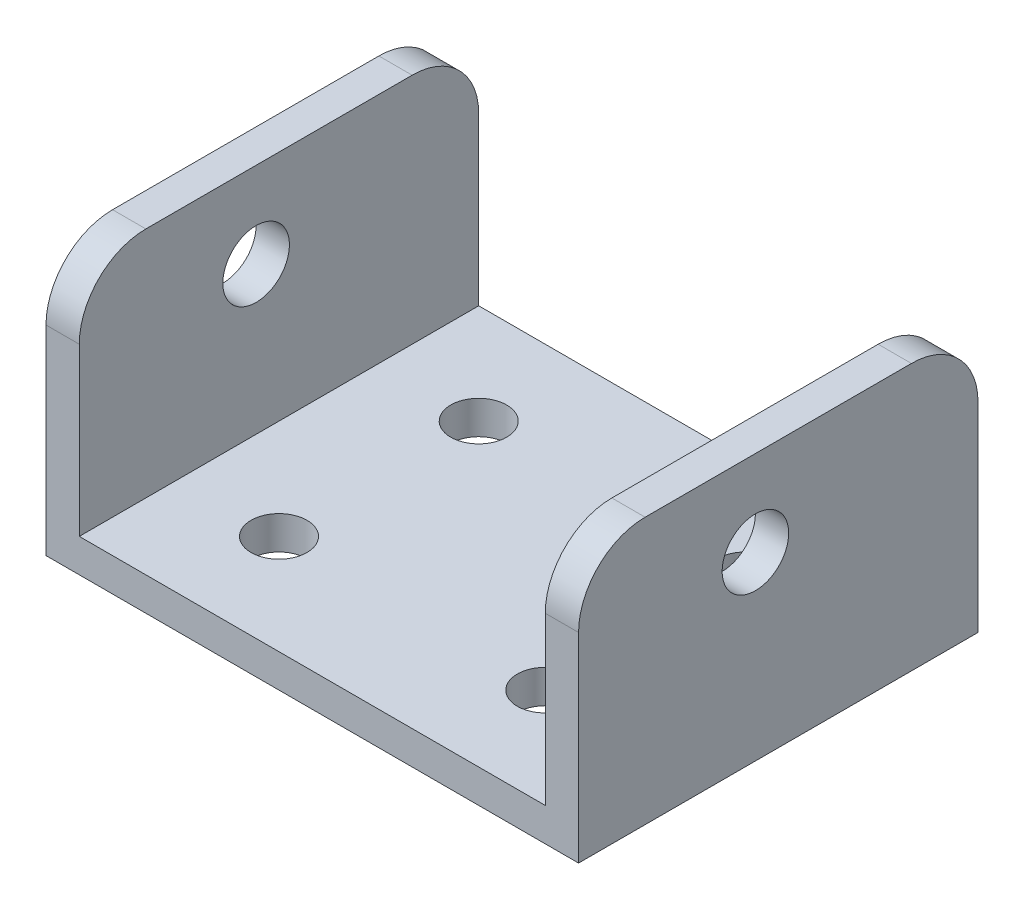
SolidWorks part; units mm, degrees
ref_plane "Front Plane" through (0, 0, 0) normal (0, 0, 1) x (1, 0, 0)
ref_plane "Top Plane" through (0, 0, 0) normal (0, 1, 0) x (1, 0, 0)
ref_plane "Right Plane" through (0, 0, 0) normal (1, 0, 0) x (0, 0, -1)
sketch "Sketch1" plane through (0, 0, 0) normal (0, 0, 1) x (1, 0, 0)
  line L0 (-22.225, -9.525) -> (-22.225, 12.7)
  line L1 (-25.4, -12.7) -> (25.4, -12.7)
  line L2 (-25.4, -12.7) -> (-25.4, 12.7)
  line L3 (-22.225, -9.525) -> (22.225, -9.525)
  line L4 (25.4, -12.7) -> (25.4, 12.7)
  line L5 (22.225, -9.525) -> (22.225, 12.7)
  line L6 (-25.4, 12.7) -> (-22.225, 12.7)
  line L7 (25.4, 12.7) -> (22.225, 12.7)
  dimension "D1" = 25.4
  dimension "D2" = 50.8
  dimension "D3" = 3.175
extrude "Boss-Extrude1" add sketch "Sketch1" along normal blind 38.1
sketch "Sketch2" plane through (-25.4, 0, 0) normal (-1, 0, 0) x (0, 0, 1)
  circle A0 centre (21.2332, 4.5432) radius 3.175 construction
  circle A1 centre (21.2332, 4.5432) radius 3.175
extrude "Cut-Extrude1" cut sketch "Sketch2" against normal through all
sketch "Sketch3" plane through (0, -9.525, 0) normal (0, 1, 0) x (1, 0, 0)
  line L0 (12.7, -14.8014) -> (22.225, -14.8014) construction
  line L1 (12.7, -9.525) -> (-12.7, -9.525) construction
  line L2 (12.7, -9.525) -> (12.7, -28.575) construction
  line L3 (12.7, -28.575) -> (-12.7, -28.575) construction
  line L4 (-12.7, -9.525) -> (-12.7, -28.575) construction
  line L5 (12.7, -9.525) -> (-12.7, -28.575) construction
  line L6 (12.7, -28.575) -> (-12.7, -9.525) construction
  line L7 (22.225, -38.1) -> (22.225, 0) construction
  line L8 (11.1432, -9.525) -> (11.1432, 0) construction
  line L9 (22.225, 0) -> (-22.225, 0) construction
  line L10 (-2.4166, -28.575) -> (-2.4166, -38.1) construction
  line L11 (22.225, -38.1) -> (-22.225, -38.1) construction
  line L12 (-12.7, -26.3921) -> (-22.225, -26.3921) construction
  line L13 (-22.225, -38.1) -> (-22.225, 0) construction
  circle A0 centre (12.7, -9.525) radius 2.667
  circle A1 centre (12.7, -28.575) radius 2.667
  circle A2 centre (-12.7, -28.575) radius 2.667
  circle A3 centre (-12.7, -9.525) radius 2.667
  point P4 (0, -19.05)
  dimension "D2" = 5.334
  dimension "D1" = 9.525
extrude "Cut-Extrude2" cut sketch "Sketch3" against normal up to next
fillet "Fillet1" radius 6.35 4 edges at (23.8125, 12.7, 38.1) (23.8125, 12.7, 0) (-23.8125, 12.7, 0) (-23.8125, 12.7, 38.1)
